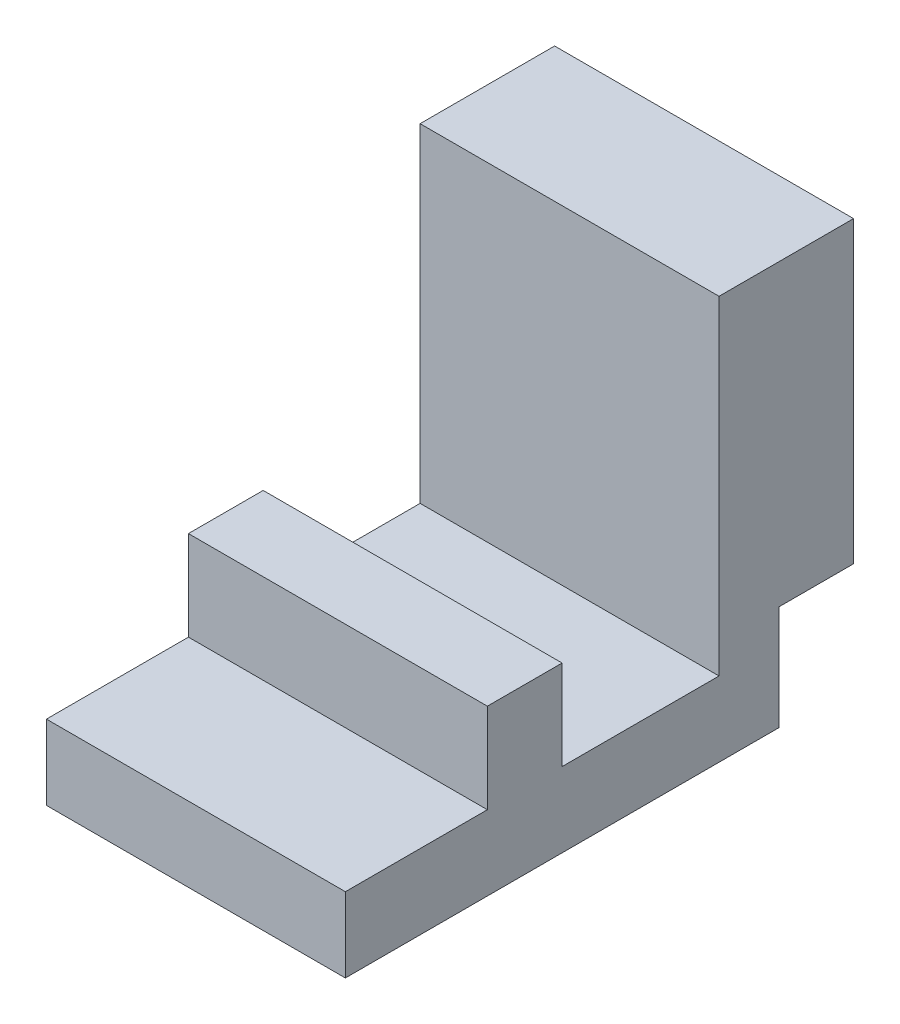
SolidWorks part; units mm, degrees
ref_plane "Front Plane" through (0, 0, 0) normal (0, 0, 1) x (1, 0, 0)
ref_plane "Top Plane" through (0, 0, 0) normal (0, 1, 0) x (1, 0, 0)
ref_plane "Right Plane" through (0, 0, 0) normal (1, 0, 0) x (0, 0, -1)
sketch "Croquis1" plane through (0, 0, 0) normal (1, 0, 0) x (0, 0, -1)
  line L0 (0, 0) -> (0, 14)
  line L1 (0, 14) -> (10, 14)
  line L2 (10, 14) -> (10, 54)
  line L3 (10, 54) -> (-8, 54)
  line L4 (-8, 54) -> (-8, 10)
  line L5 (-8, 10) -> (-29, 10)
  line L6 (-29, 10) -> (-29, 22)
  line L7 (-29, 22) -> (-39, 22)
  line L8 (-39, 22) -> (-39, 10)
  line L9 (-39, 10) -> (-58, 10)
  line L10 (-58, 10) -> (-58, 0)
  line L11 (-58, 0) -> (0, 0)
  point P9 (-29, 16)
  dimension "D1" = 54
  dimension "D2" = 18
  dimension "D3" = 14
  dimension "D4" = 10
  dimension "D5" = 10
  dimension "D6" = 10
  dimension "D7" = 39
  dimension "D8" = 10
  dimension "D9" = 22
  dimension "D10" = 68
  dimension "D11" = 8
extrude "Saliente-Extruir2" add sketch "Croquis1" along normal mid plane 40
sketch "Croquis4" plane through (0, 0, 8) normal (0, 0, 1) x (1, 0, 0)
  line L0 (20, 10) -> (-20, 10) construction
  circle A0 centre (0, 44) radius 13
  dimension "D2" = 26
  dimension "D1" = 34
